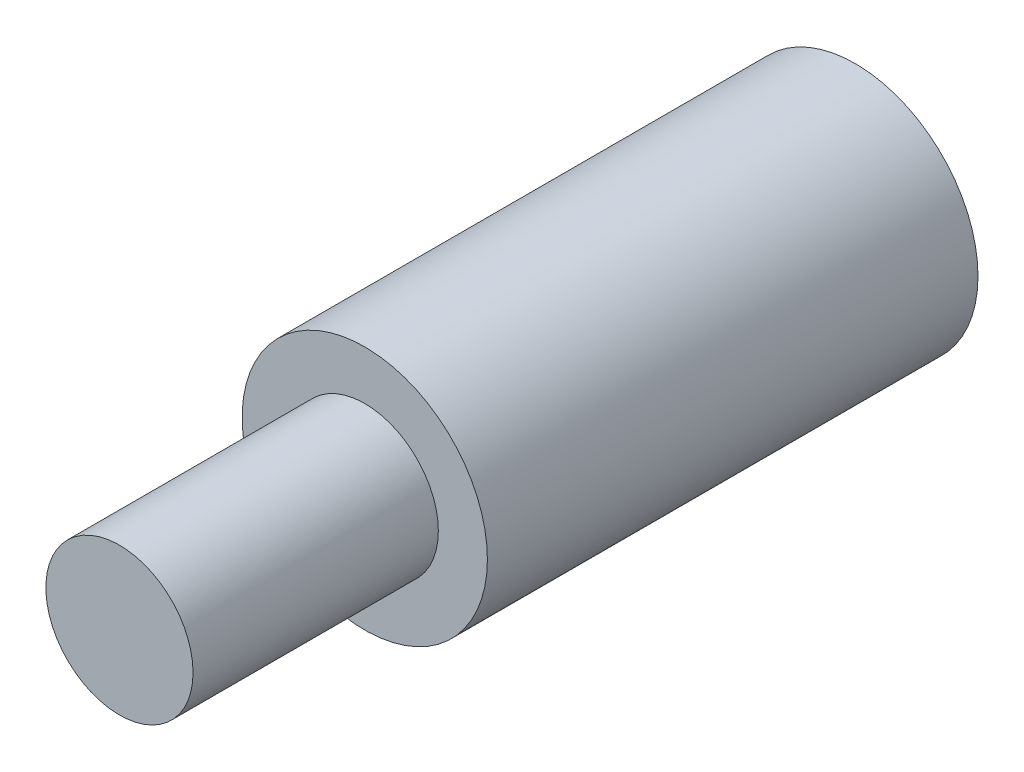
SolidWorks part; units mm, degrees
ref_plane "Front Plane" through (0, 0, 0) normal (0, 0, 1) x (1, 0, 0)
ref_plane "Top Plane" through (0, 0, 0) normal (0, 1, 0) x (1, 0, 0)
ref_plane "Right Plane" through (0, 0, 0) normal (1, 0, 0) x (0, 0, -1)
sketch "Sketch1" plane through (0, 0, 0) normal (0, 0, 1) x (1, 0, 0)
  circle A0 centre (0, 0) radius 2.5
  dimension "D1" = 5
extrude "Boss-Extrude1" add sketch "Sketch1" along normal blind 10
sketch "Sketch2" plane through (0, 0, 10) normal (0, 0, 1) x (1, 0, 0)
  circle A0 centre (0, 0) radius 1.5
  dimension "D1" = 3
extrude "Boss-Extrude2" add sketch "Sketch2" along normal blind 5
sketch "Sketch3" plane through (0, 0, 0) normal (0, 0, -1) x (-1, 0, 0)
  circle A0 centre (0, 0) radius 1.5
  dimension "D1" = 3
extrude "Cut-Extrude1" cut sketch "Sketch3" against normal blind 5
